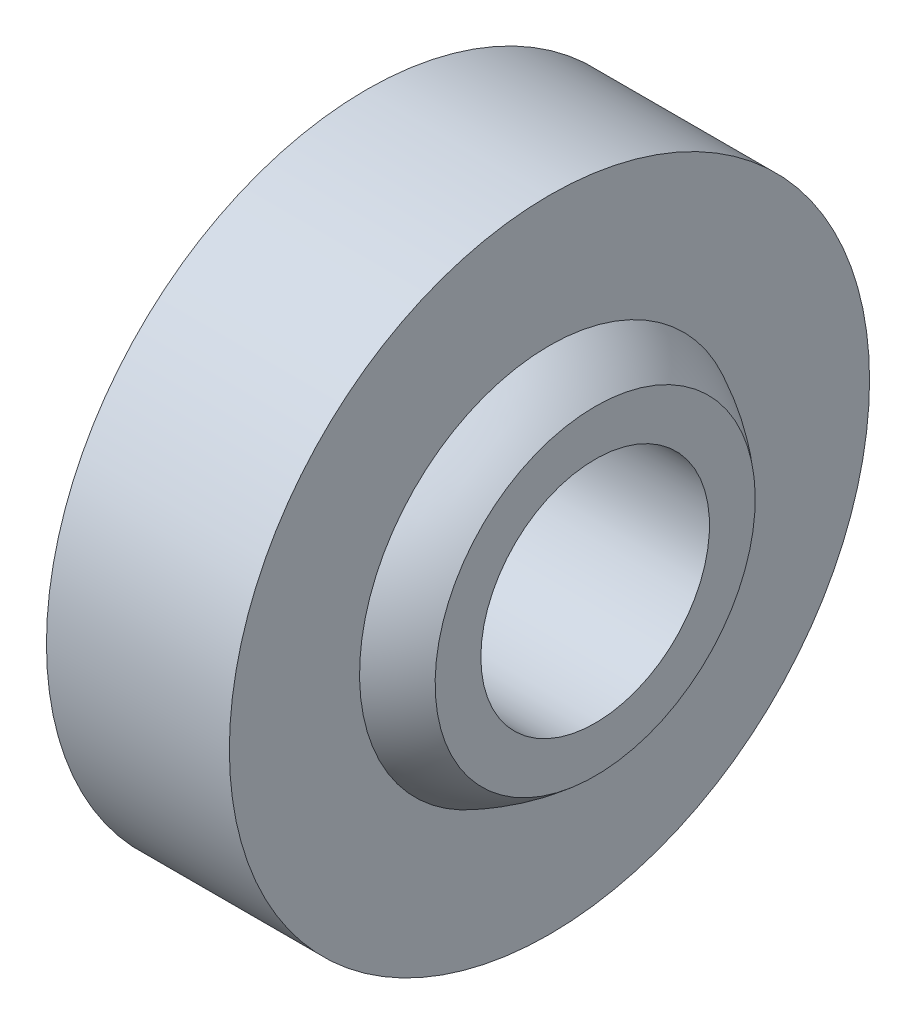
SolidWorks part; units mm, degrees
material "合金钢"
ref_plane "前视基准面" through (0, 0, 0) normal (0, 0, 1) x (1, 0, 0)
ref_plane "上视基准面" through (0, 0, 0) normal (0, 1, 0) x (1, 0, 0)
ref_plane "右视基准面" through (0, 0, 0) normal (1, 0, 0) x (0, 0, -1)
other "Configuration Table"
sketch "草图1" plane through (0, 0, 0) normal (0, 0, 1) x (1, 0, 0)
  line L0 (-2.9558, 0) -> (2.3907, 0) construction
  line L1 (0, 1.717) -> (0, -2.3038) construction
  line L2 (-3, 2.5) -> (3, 2.5)
  line L3 (-3, 3.5) -> (-3, 2.5)
  line L4 (3, 3.5) -> (3, 2.5)
  arc A0 (3, 3.5) -> (-3, 3.5) centre (0, 0) ccw
  point P8 (0, 5.2494)
  point P12 (0, 2.5)
  dimension "D1" = 7
  dimension "D2" = 5
  dimension "D3" = 6
revolve "旋转1" add sketch "草图1" angle 360 about L0
sketch "草图3" plane through (0, 0, 0) normal (0, 0, 1) x (1, 0, 0)
  line L0 (0, 6.3041) -> (0, 2.2339) construction
  line L1 (-2, 7) -> (2, 7)
  line L2 (-2, 7) -> (-2, 4.1533)
  line L3 (-2, 4.1533) -> (2, 4.1533)
  line L4 (2, 7) -> (2, 4.1533)
  line L5 (-4.3558, 0) -> (8.3455, 0) construction
  arc A0 (3, 3.5) -> (-3, 3.5) centre (0, 0) ccw construction
  dimension "D1" = 4
  dimension "D2" = 7
revolve "旋转2" add sketch "草图3" angle 360 about L5
